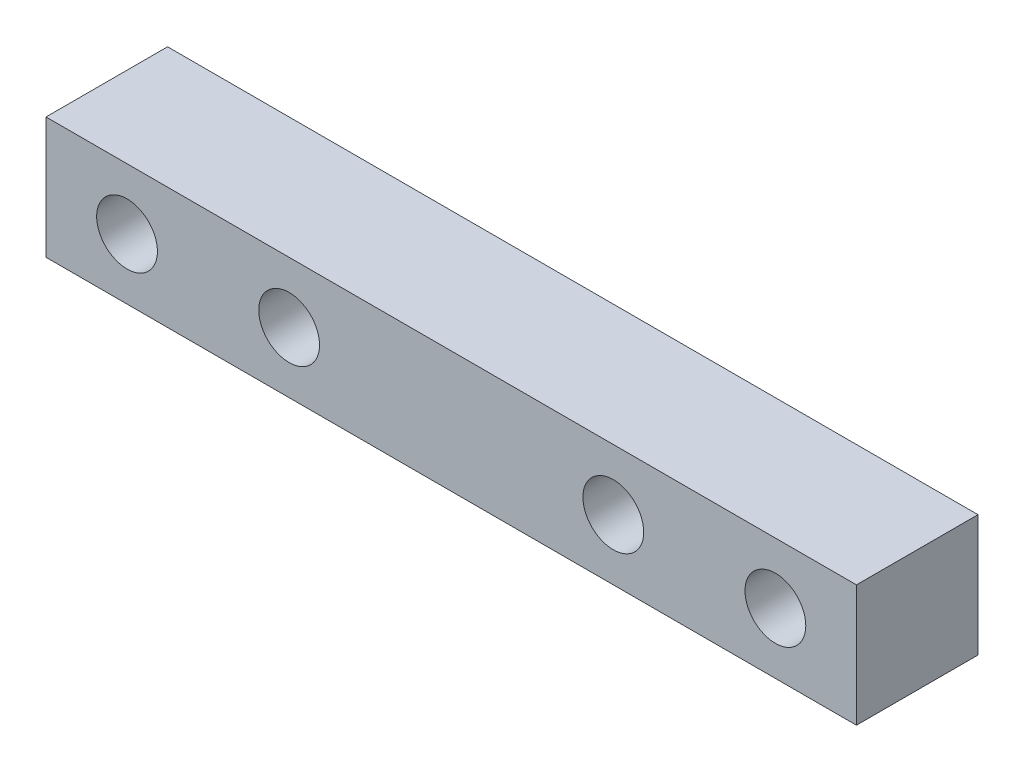
SolidWorks part; units mm, degrees
material "6061-T6 (SS)"
ref_plane "前视基准面" through (0, 0, 0) normal (0, 0, 1) x (1, 0, 0)
ref_plane "上视基准面" through (0, 0, 0) normal (0, 1, 0) x (1, 0, 0)
ref_plane "右视基准面" through (0, 0, 0) normal (1, 0, 0) x (0, 0, -1)
sketch "草图1" plane through (0, 0, 0) normal (0, 0, 1) x (1, 0, 0)
  line L0 (-16, 0) -> (16, 0) construction
  line L1 (20, -3) -> (-20, -3)
  line L2 (20, -3) -> (20, 3)
  line L3 (20, 3) -> (-20, 3)
  line L4 (-20, -3) -> (-20, 3)
  line L5 (20, -3) -> (-20, 3) construction
  line L6 (20, 3) -> (-20, -3) construction
  line L7 (-8, 0) -> (8, 0) construction
  circle A0 centre (-16, 0) radius 1.25
  circle A1 centre (16, 0) radius 1.25
  circle A2 centre (-8, 0) radius 1.25
  circle A3 centre (8, 0) radius 1.25
  point P0 (0, 0)
  dimension "D4" = 2.5
  dimension "D1" = 40
  dimension "D2" = 6
  dimension "D3" = 32
  dimension "D5" = 16
extrude "凸台-拉伸1" add sketch "草图1" along normal blind 6
sketch "草图3" plane through (0, 0, 6) normal (0, 0, 1) x (1, 0, 0)
  circle A0 centre (-16, 0) radius 1.5
  circle A1 centre (-8, 0) radius 1.5
  circle A2 centre (8, 0) radius 1.5
  circle A3 centre (16, 0) radius 1.5
  dimension "D1" = 3
extrude "切除-拉伸1" cut sketch "草图3" against normal through all
